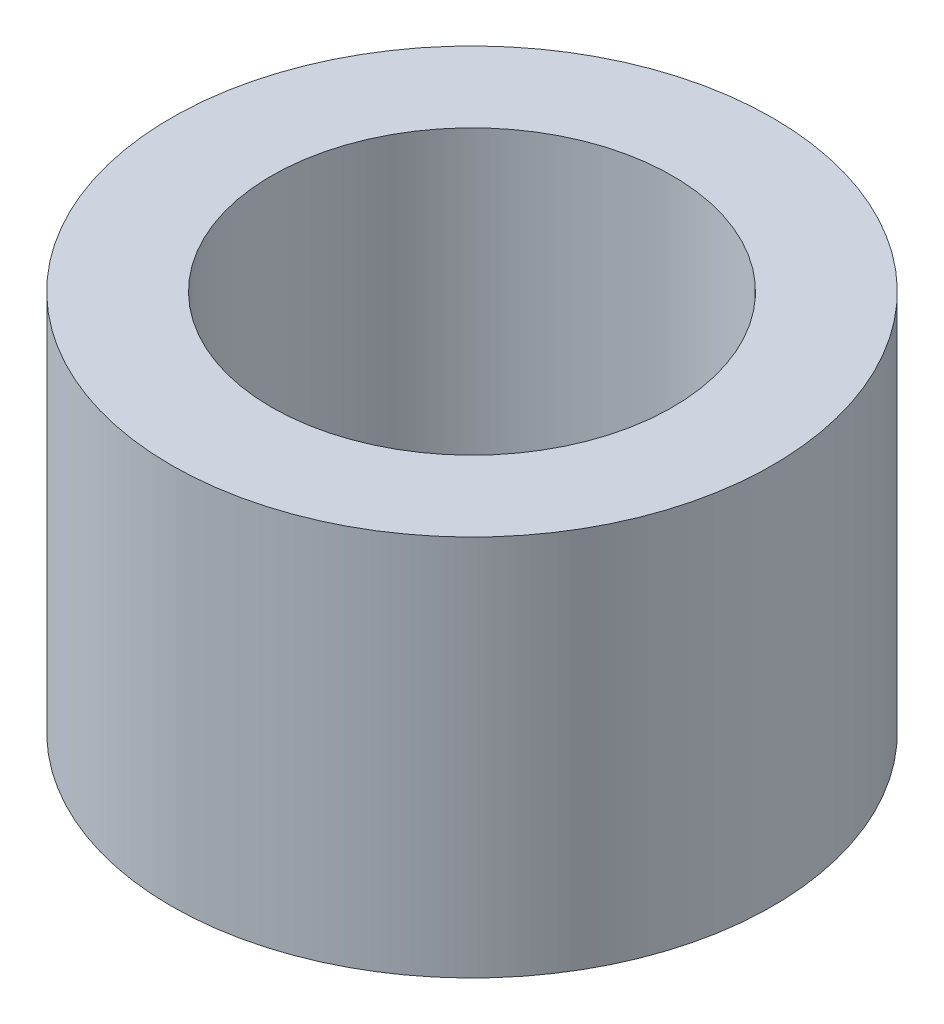
SolidWorks part; units mm, degrees
ref_plane "Front Plane" through (0, 0, 0) normal (0, 0, 1) x (1, 0, 0)
ref_plane "Top Plane" through (0, 0, 0) normal (0, 1, 0) x (1, 0, 0)
ref_plane "Right Plane" through (0, 0, 0) normal (1, 0, 0) x (0, 0, -1)
sketch "Sketch1" plane through (0, 0, 0) normal (0, 1, 0) x (1, 0, 0)
  circle A0 centre (0, 0) radius 3.15
  circle A1 centre (0, 0) radius 2.1
  dimension "D1" = 6.3
  dimension "D2" = 4.2
extrude "Boss-Extrude1" add sketch "Sketch1" along normal blind 4 contours A0 A1
